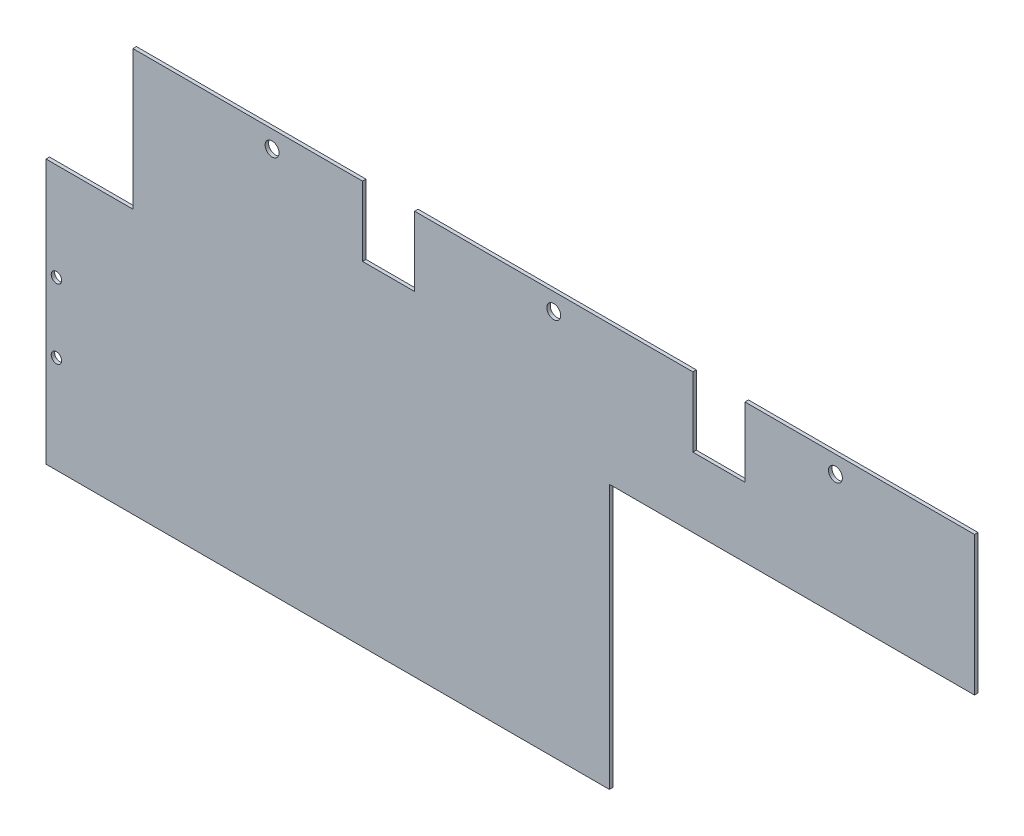
SolidWorks part; units mm, degrees
material "Thornel Mat VMA"
ref_plane "前视基准面" through (0, 0, 0) normal (0, 0, 1) x (1, 0, 0)
ref_plane "上视基准面" through (0, 0, 0) normal (0, 1, 0) x (1, 0, 0)
ref_plane "右视基准面" through (0, 0, 0) normal (1, 0, 0) x (0, 0, -1)
sketch "草图1" plane through (0, 0, 0) normal (0, 0, 1) x (1, 0, 0)
  line L0 (0, 0) -> (0, 76)
  line L1 (0, 76) -> (25, 76)
  line L2 (25, 76) -> (25, 116)
  line L3 (25, 116) -> (267, 116)
  line L4 (267, 116) -> (267, 76)
  line L5 (267, 76) -> (292, 76)
  line L6 (292, 76) -> (292, 0)
  line L7 (292, 0) -> (0, 0)
  line L8 (3, 48) -> (3, 28) construction
  line L9 (0, 38) -> (292, 38) construction
  line L10 (146, 116) -> (146, 0) construction
  line L11 (289, 48) -> (289, 28) construction
  circle A0 centre (3, 48) radius 1.5
  circle A1 centre (3, 28) radius 1.5
  circle A2 centre (289, 28) radius 1.5
  circle A3 centre (289, 48) radius 1.5
  point P13 (3, 38)
  dimension "D7" = 3
  dimension "D1" = 292
  dimension "D2" = 76
  dimension "D3" = 40
  dimension "D4" = 25
  dimension "D5" = 20
  dimension "D6" = 3
extrude "凸台-拉伸1" add sketch "草图1" along normal blind 1
sketch "草图2" plane through (0, 0, 1) normal (0, 0, 1) x (1, 0, 0)
  line L0 (146, 116) -> (146, 0) construction
  line L1 (267, 116) -> (25, 116) construction
  line L2 (0, 0) -> (292, 0) construction
  line L3 (186, 116) -> (186, 96)
  line L4 (91, 116) -> (106, 116)
  line L5 (91, 116) -> (91, 96)
  line L6 (91, 96) -> (106, 96)
  line L7 (106, 116) -> (106, 96)
  line L8 (201, 96) -> (186, 96)
  line L9 (201, 116) -> (201, 96)
  line L10 (201, 116) -> (186, 116)
  line L11 (25, 116) -> (25, 76) construction
  circle A0 centre (65, 111) radius 2
  circle A1 centre (227, 111) radius 2
  circle A2 centre (146, 111) radius 2
  point P14 (98.5, 116)
  point P15 (193.5, 116)
  dimension "D4" = 4
  dimension "D7" = 4
  dimension "D1" = 95
  dimension "D2" = 15
  dimension "D3" = 20
  dimension "D5" = 5
  dimension "D6" = 40
extrude "切除-拉伸1" cut sketch "草图2" against normal through all
sketch "草图3" plane through (0, 0, 1) normal (0, 0, 1) x (1, 0, 0)
  line L0 (292, 76) -> (267, 76) construction
  line L1 (292, 0) -> (162, 0)
  line L2 (292, 0) -> (292, 76)
  line L3 (292, 76) -> (162, 76)
  line L4 (162, 0) -> (162, 76)
  line L5 (292, 0) -> (292, 76) construction
  dimension "D1" = 130
extrude "切除-拉伸2" cut sketch "草图3" against normal through all
